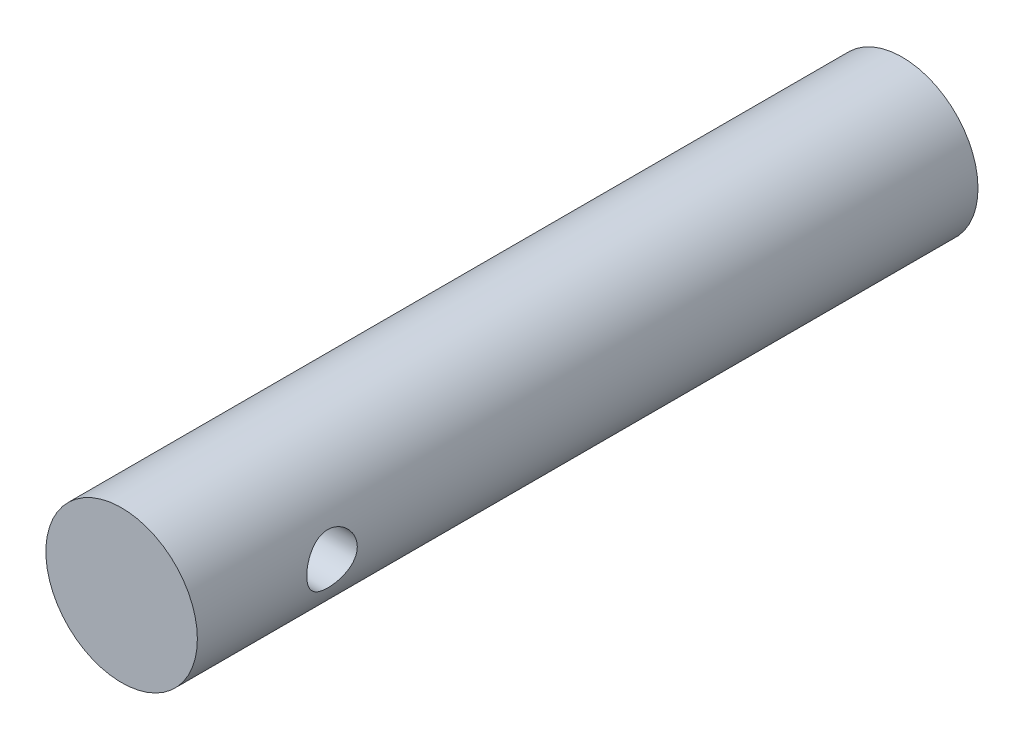
SolidWorks part; units mm, degrees
ref_plane "Plane1" through (0, 0, 0) normal (0, 0, 1) x (1, 0, 0)
ref_plane "Plane2" through (0, 0, 0) normal (0, 1, 0) x (1, 0, 0)
ref_plane "Plane3" through (0, 0, 0) normal (1, 0, 0) x (0, 0, -1)
other "Configuration Table"
sketch "Sketch1" plane through (0, 0, 0) normal (0, 0, 1) x (1, 0, 0)
  circle A0 centre (0, 0) radius 5.715
  dimension "D1" = 11.43
extrude "Base-Extrude" add sketch "Sketch1" against normal blind 58.8909
sketch "Sketch2" plane through (0, 0, 0) normal (1, 0, 0) x (0, 0, -1)
  circle A0 centre (10.16, 0) radius 1.905
  circle A1 centre (-33.8292, 0) radius 1.905 construction
  dimension "D1" = 10.16
extrude "Cut-Extrude1" cut sketch "Sketch2" against normal through all and the other way through all
